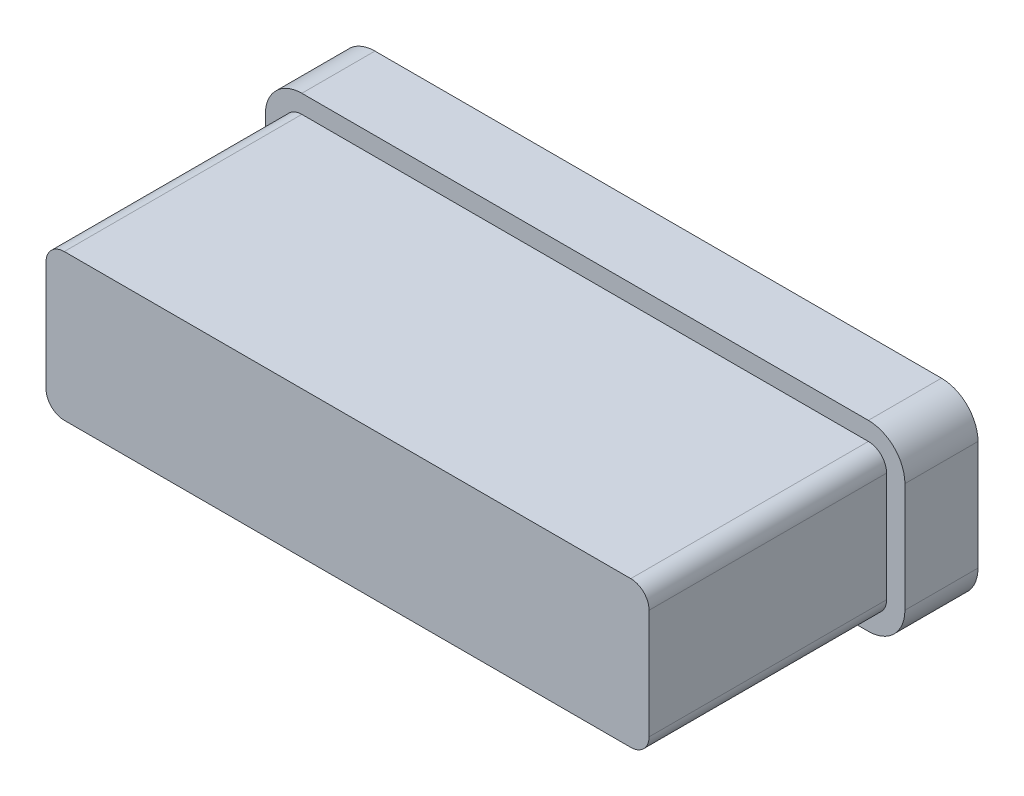
SolidWorks part; units mm, degrees
ref_plane "Top Plane" through (0, 0, 0) normal (0, 0, 1) x (1, 0, 0)
ref_plane "Front Plane" through (0, 0, 0) normal (0, 1, 0) x (1, 0, 0)
ref_plane "Right Plane" through (0, 0, 0) normal (1, 0, 0) x (0, 0, -1)
sketch "Sketch2" plane through (0, 0, 0) normal (0, 0, 1) x (1, 0, 0)
  line L1 (-17.5, -5) -> (17.5, -5)
  line L2 (-17.5, -5) -> (-17.5, 5)
  line L3 (-17.5, 5) -> (17.5, 5)
  line L4 (17.5, -5) -> (17.5, 5)
  line L5 (-17.5, -5) -> (17.5, 5) construction
  line L6 (-17.5, 5) -> (17.5, -5) construction
  point P0 (0, 0)
  dimension "D1" = 10
  dimension "D2" = 35
extrude "Boss-Extrude1" add sketch "Sketch2" along normal blind 4
fillet "Fillet1" radius 2 4 edges at (-17.5, -5, 2) (-17.5, 5, 2) (17.5, -5, 2) (17.5, 5, 2)
sketch "Sketch3" plane through (0, 0, 4) normal (0, 0, 1) x (1, 0, 0)
  line L8 (-16.5, 3) -> (-16.5, -3)
  line L9 (-15.5, -4) -> (15.5, -4)
  line L10 (16.5, -3) -> (16.5, 3)
  line L11 (15.5, 4) -> (-15.5, 4)
  line L12 (-16.5, 3) -> (-16.5, -3)
  line L13 (-15.5, -4) -> (15.5, -4)
  line L14 (16.5, -3) -> (16.5, 3)
  line L15 (15.5, 4) -> (-15.5, 4)
  arc A8 (-16.5, -3) -> (-15.5, -4) centre (-15.5, -3) ccw
  arc A9 (15.5, -4) -> (16.5, -3) centre (15.5, -3) ccw
  arc A10 (16.5, 3) -> (15.5, 4) centre (15.5, 3) ccw
  arc A11 (-15.5, 4) -> (-16.5, 3) centre (-15.5, 3) ccw
  arc A12 (-16.5, -3) -> (-15.5, -4) centre (-15.5, -3) ccw
  arc A13 (15.5, -4) -> (16.5, -3) centre (15.5, -3) ccw
  arc A14 (16.5, 3) -> (15.5, 4) centre (15.5, 3) ccw
  arc A15 (-15.5, 4) -> (-16.5, 3) centre (-15.5, 3) ccw
  dimension "D1" = 1
extrude "Boss-Extrude2" add sketch "Sketch3" along normal blind 13
